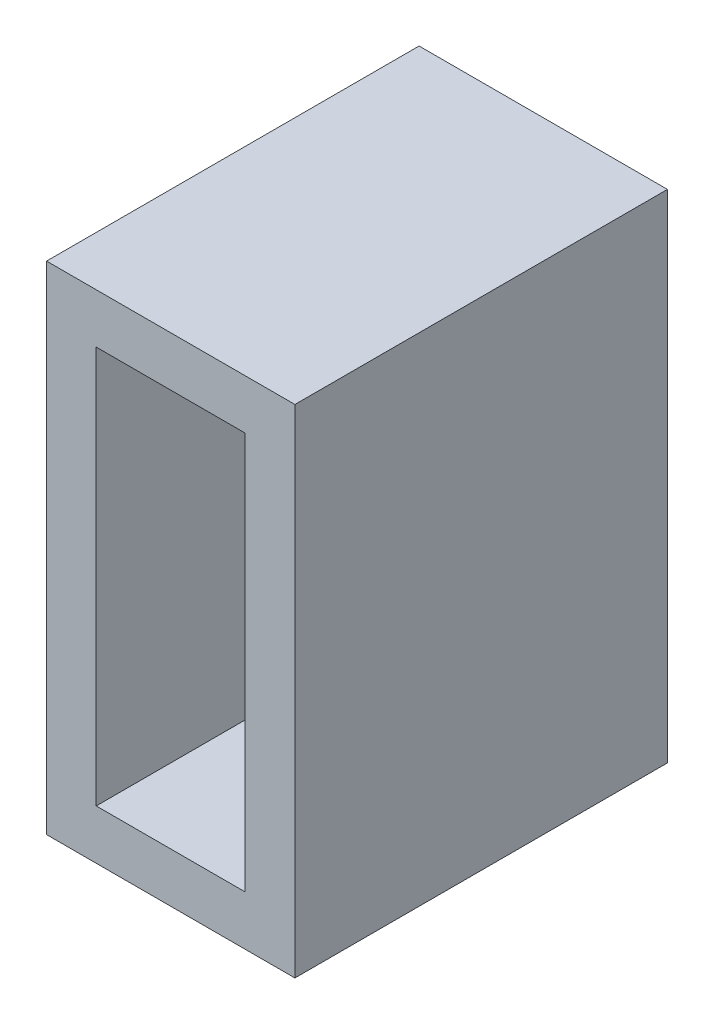
SolidWorks part; units mm, degrees
ref_plane "Front Plane" through (0, 0, 0) normal (0, 0, 1) x (1, 0, 0)
ref_plane "Top Plane" through (0, 0, 0) normal (0, 1, 0) x (1, 0, 0)
ref_plane "Right Plane" through (0, 0, 0) normal (1, 0, 0) x (0, 0, -1)
sketch "Sketch1" plane through (0, 0, 0) normal (0, 0, 1) x (1, 0, 0)
  line L1 (-7.62, -20.32) -> (7.62, -20.32)
  line L2 (-7.62, -20.32) -> (-7.62, 20.32)
  line L3 (-7.62, 20.32) -> (7.62, 20.32)
  line L4 (7.62, -20.32) -> (7.62, 20.32)
  line L5 (-7.62, -20.32) -> (7.62, 20.32) construction
  line L6 (-7.62, 20.32) -> (7.62, -20.32) construction
  line L7 (-12.7, -25.4) -> (12.7, -25.4)
  line L8 (-12.7, -25.4) -> (-12.7, 25.4)
  line L9 (-12.7, 25.4) -> (12.7, 25.4)
  line L10 (12.7, -25.4) -> (12.7, 25.4)
  line L11 (-12.7, -25.4) -> (12.7, 25.4) construction
  line L12 (-12.7, 25.4) -> (12.7, -25.4) construction
  point P0 (0, 0)
  point P6 (0, 0)
  dimension "D1" = 50.8
  dimension "D2" = 5.08
  dimension "D3" = 5.08
  dimension "D4" = 25.4
extrude "Boss-Extrude1" add sketch "Sketch1" along normal blind 38.1
